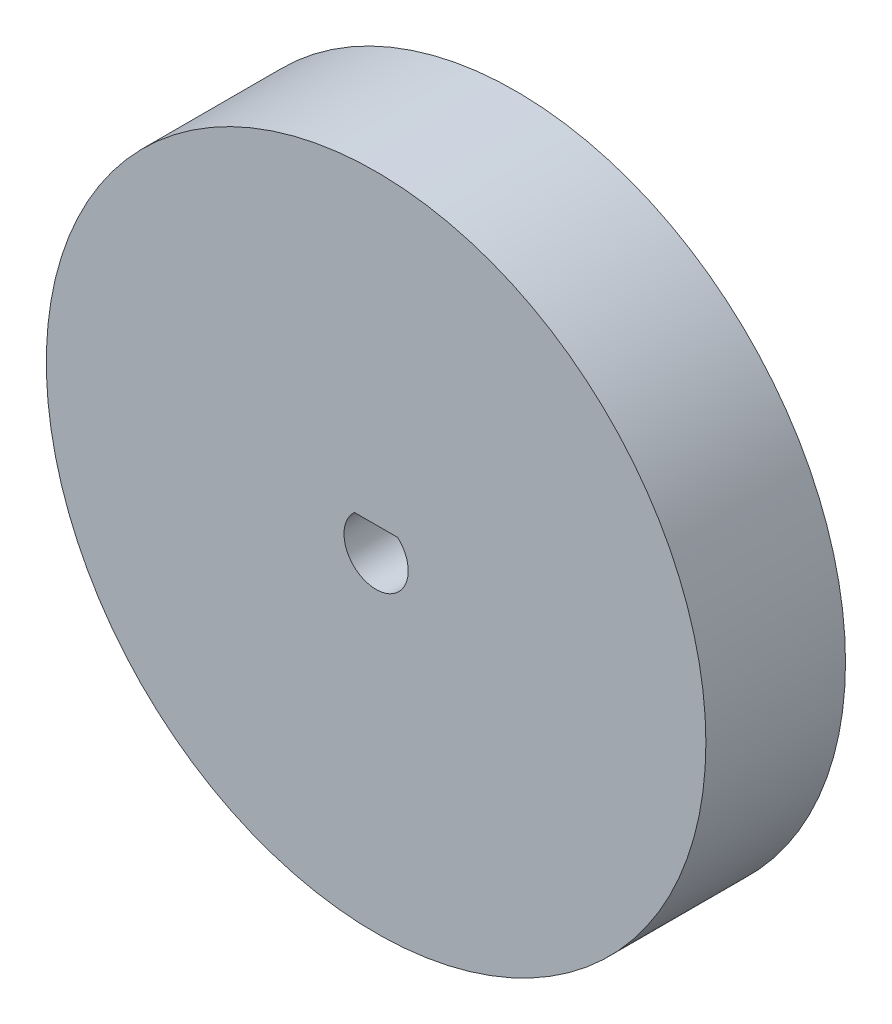
SolidWorks part; units mm, degrees
ref_plane "Front Plane" through (0, 0, 0) normal (0, 0, 1) x (1, 0, 0)
ref_plane "Top Plane" through (0, 0, 0) normal (0, 1, 0) x (1, 0, 0)
ref_plane "Right Plane" through (0, 0, 0) normal (1, 0, 0) x (0, 0, -1)
sketch "Sketch1" plane through (0, 0, 0) normal (0, 0, 1) x (1, 0, 0)
  circle A0 centre (0, 0) radius 30
  dimension "D1" = 60
extrude "Boss-Extrude1" add sketch "Sketch1" along normal blind 12.7
sketch "Sketch2" plane through (0, 0, 0) normal (0, 0, -1) x (-1, 0, 0)
  line L1 (-1.9675, 2.159) -> (1.9675, 2.159)
  line L2 (-1.9675, 2.159) -> (-1.9675, 2.921) construction
  line L3 (-1.9675, 2.921) -> (1.9675, 2.921) construction
  line L4 (1.9675, 2.159) -> (1.9675, 2.921) construction
  circle A0 centre (0, 0) radius 2.921 construction
  arc A1 (1.9675, 2.159) -> (-1.9675, 2.159) centre (0, 0) cw
  point P10 (0, 2.921)
  dimension "D2" = 5.842
  dimension "D1" = 5.08
extrude "Cut-Extrude1" cut sketch "Sketch2" against normal through all contours A1 L1
equation "\"FoamCore\" = \".2\""
equation "\"MDF\" = \".2\""
equation "\"GMaterial\"= \".2\""
equation "\"PVCMountDiameter\" = \"0.5in\""
equation "\"PVCMountDistanceToEdge\" = \"0.5\""
equation "\"PVCThickness\" = \"0.13in\""
equation "\"BaseWidth\" = \"8in\""
equation "\"BaseLength\" = \"10in\""
equation "\"BallDiameter\" = \"1.57in\""
equation "\"BaseGap\" = \"4in\""
equation "\"FunnelTopDiameter\" = \"8in\""
equation "\"FunnelTopDepth\" = \"1.5in\""
equation "\"BallGap\" = \"0.1in\""
equation "\"FunnelLength\" = 6in"
equation "\"FunnelMaterial\" = 0.1in"
equation "\"FunnelLowerDiameter\" = \"PVCDiameter\" + \"PVCThickness\"*2"
equation "\"FunnelDepth\" = 1.5in"
equation "\"AmmoFeederLength\" = 1in + 76mm"
equation "\"AmmoFeederCutoffLength\" = \"MovingWheelDiameter\""
equation "\"WheelThickness\" = 0.5in"
equation "\"D1@Boss-Extrude1\"=\"WheelThickness\""
equation "\"LauncherWheelDiameter\" = 60mm"
equation "\"D1@Sketch1\"=\"LauncherWheelDiameter\""
equation "\"MotorDriveshaft\"= 16mm"
equation "\"MotorFlatDiameter\"= 11mm"
equation "\"D2@Sketch2\"=\"MotorDriveshaftDiameter\""
equation "\"MotorFrontLength\" = 0.95in"
equation "\"MotorBodyTotalLength\" = 2.03in"
equation "\"MotorFrontDiameter\" = 1.5in"
equation "\"MotorLowerDriveshaftDiameter\" = 0.46in"
equation "\"MotorLowerDriveshaftThickness\" = 0.25in"
equation "\"MotorFullDriveshaftLength\" = 0.78in"
equation "\"MotorDriveshaftDiameter\" = 0.23in"
equation "\"MotorDriveshaftFlatThickness\" = 0.2in"
equation "\"MotorRearDiameter\" = 31.9mm"
equation "\"MotorDriveshaftBottomToTop\" = 31.1mm"
equation "\"MotorFlatDriveshaftLength\" = 11.7mm"
equation "\"MotorDistanceBetweenLowerandTopHoles\" = 0.5in"
equation "\"MotorMountsDistanceFromEdge\" = 0.06in"
equation "\"MotorScrewMountDiameter\" = 0.1in"
equation "\"MotorScrewMountDepth\" = 0.13in"
equation "\"HBRidgeScrewHoleDeep\" = 0.18in"
equation "\"D1@Sketch2\"=\"MotorDriveshaftFlatThickness\""
